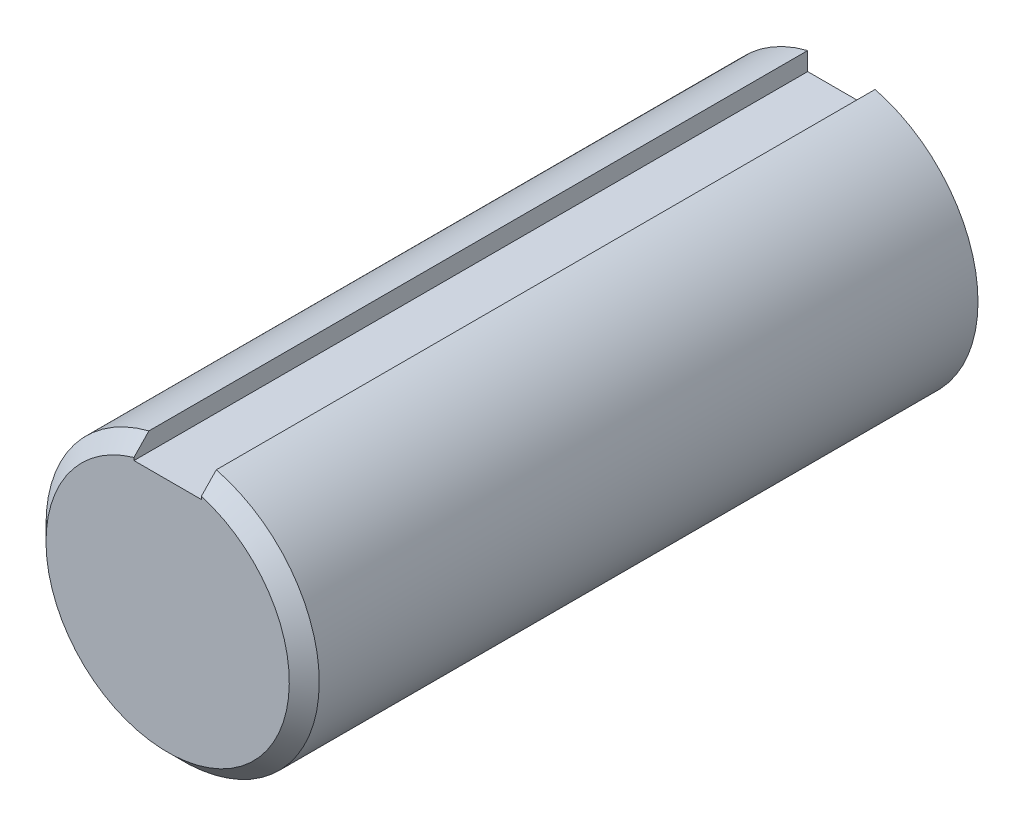
SolidWorks part; units mm, degrees
ref_plane "Front Plane" through (0, 0, 0) normal (0, 0, 1) x (1, 0, 0)
ref_plane "Top Plane" through (0, 0, 0) normal (0, 1, 0) x (1, 0, 0)
ref_plane "Right Plane" through (0, 0, 0) normal (1, 0, 0) x (0, 0, -1)
sketch "Sketch1" plane through (0, 0, 0) normal (0, 0, 1) x (1, 0, 0)
  circle A0 centre (0, 0) radius 18.25
  dimension "D1" = 36.5
extrude "Boss-Extrude1" add sketch "Sketch1" along normal blind 90
sketch "Sketch2" plane through (0, 0, 90) normal (0, 0, 1) x (1, 0, 0)
  line L1 (-4.5, 21.25) -> (4.5, 21.25)
  line L2 (-4.5, 21.25) -> (-4.5, 15.25)
  line L3 (-4.5, 15.25) -> (4.5, 15.25)
  line L4 (4.5, 21.25) -> (4.5, 15.25)
  point P4 (0, 0)
  dimension "D1" = 9
  dimension "D2" = 6
  dimension "D3" = 15.25
extrude "Cut-Extrude1" cut sketch "Sketch2" against normal through all
chamfer "Chamfer1" distance 2 angle 45 1 edges at (0, -18.25, 90)
